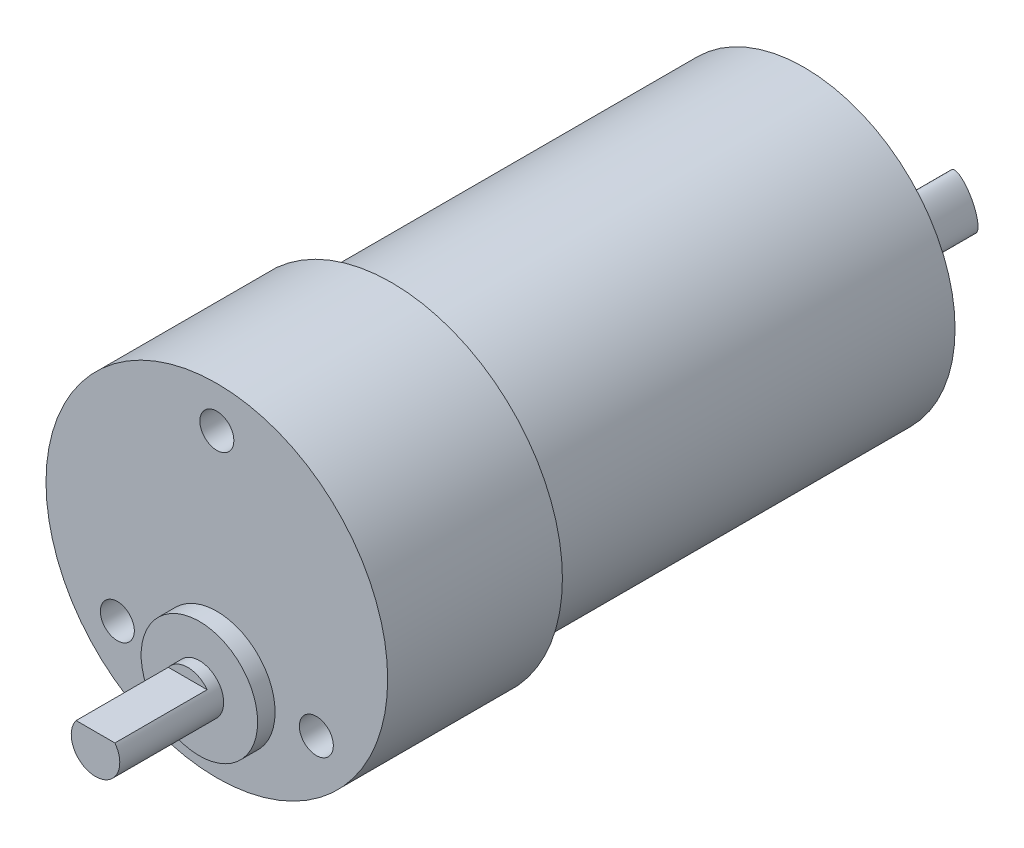
SolidWorks part; units mm, degrees
ref_plane "Front Plane" through (0, 0, 0) normal (0, 0, 1) x (1, 0, 0)
ref_plane "Top Plane" through (0, 0, 0) normal (0, 1, 0) x (1, 0, 0)
ref_plane "Right Plane" through (0, 0, 0) normal (1, 0, 0) x (0, 0, -1)
sketch "Sketch1" plane through (0, 0, 0) normal (0, 0, 1) x (1, 0, 0)
  circle A0 centre (0, 0) radius 15.55
  dimension "D1" = 31.1
extrude "Back" add sketch "Sketch1" against normal blind 42.5
sketch "Sketch3" plane through (0, 0, 0) normal (0, 0, 1) x (1, 0, 0)
  circle A0 centre (0, 0) radius 17.6
  dimension "D1" = 35.2
extrude "Front" add sketch "Sketch3" along normal blind 18
sketch "Sketch4" plane through (0, 0, 18) normal (0, 0, 1) x (1, 0, 0)
  line L0 (-19.8, 0) -> (20.0731, 0) construction
  line L1 (0, 18.5938) -> (0, -19.6407) construction
  line L2 (27.4468, 0) -> (27.4468, -8.73) construction
  line L3 (27.4468, -8.73) -> (-19.8, -8.73) construction
  circle A0 centre (0, -8.73) radius 6
  dimension "D2" = 12
  dimension "D1" = 8.73
extrude "ShaftBearing" add sketch "Sketch4" along normal blind 1.8
sketch "Sketch5" plane through (0, 0, 18) normal (0, 0, 1) x (1, 0, 0)
  line L0 (-20.3773, 0) -> (20.6887, 0) construction
  line L1 (0, 19.4837) -> (0, -19.5833) construction
  line L2 (24.3117, 0) -> (24.3117, -8.73) construction
  line L3 (24.3117, -8.73) -> (-20.3773, -8.73) construction
  line L4 (30.8328, -8.73) -> (30.8328, 13.37) construction
  line L5 (30.8328, 13.37) -> (-17.1985, 13.37) construction
  line L6 (0, -21.156) -> (10.25, -21.156) construction
  line L7 (0, -21.156) -> (-10.25, -21.156) construction
  line L8 (-10.25, -21.156) -> (-10.25, -3.2566) construction
  line L9 (10.25, -21.156) -> (10.25, -3.2566) construction
  circle A0 centre (-10.25, -8.73) radius 1.75
  circle A1 centre (10.25, -8.73) radius 1.75
  circle A2 centre (0, 13.37) radius 1.75
  dimension "D5" = 3.5
  dimension "D6" = 3.5
  dimension "D7" = 3.5
  dimension "D1" = 8.73
  dimension "D2" = 22.1
  dimension "D3" = 10.25
  dimension "D4" = 10.25
extrude "frontScrewHoles" cut sketch "Sketch5" against normal blind 5.5
sketch "Sketch6" plane through (0, 0, 19.8) normal (0, 0, 1) x (1, 0, 0)
  line L0 (-7.2372, -8.73) -> (6.9641, -8.73) construction
  line L1 (0, -1.8434) -> (0, -18.5027) construction
  circle A0 centre (0, -8.73) radius 2.5
  dimension "D1" = 5
extrude "RoundPartofShaft" add sketch "Sketch6" along normal blind 1.2
sketch "Sketch7" plane through (0, 0, 21) normal (0, 0, 1) x (1, 0, 0)
  line L0 (-3.9607, -11.23) -> (3.8566, -11.23) construction
  line L1 (3.8566, -11.23) -> (3.8566, -7.23) construction
  line L2 (2, -7.23) -> (-2, -7.23)
  arc A0 (-2, -7.23) -> (2, -7.23) centre (0, -8.73) ccw
  dimension "D1" = 4
extrude "FlatPartofShaft" add sketch "Sketch7" along normal blind 9.5
sketch "Sketch8" plane through (0, 0, -42.5) normal (0, 0, -1) x (-1, 0, 0)
  line L0 (-23.2135, 0) -> (20.2704, 0) construction
  line L1 (0, -20.2769) -> (0, 14.947) construction
  line L2 (0, 0) -> (8.3927, -4.2763) construction
  line L3 (0, 0) -> (-27.9891, 14.2612) construction
  line L4 (0, 0) -> (8.3927, 16.4715) construction
  circle A0 centre (0, 0) radius 10.6 construction
  ellipse E0 centre (9.443, -4.8155) end of major axis (8.2832, -7.0899) minor radius 1.012
  ellipse E1 centre (-9.4463, 4.8091) end of major axis (-8.288, 7.0842) minor radius 1.012
  dimension "D1" = 21.2
  dimension "D2" = 27
extrude "Pwr And Gnd" add sketch "Sketch8" along normal blind 7
